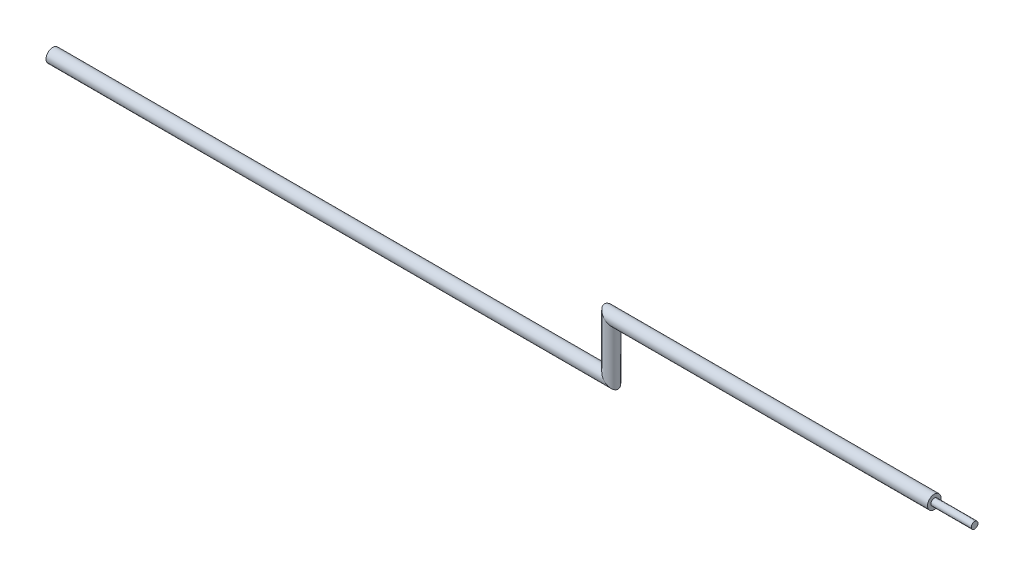
SolidWorks part; units mm, degrees
ref_plane "Front Plane" through (0, 0, 0) normal (0, 0, 1) x (1, 0, 0)
ref_plane "Top Plane" through (0, 0, 0) normal (0, 1, 0) x (1, 0, 0)
ref_plane "Right Plane" through (0, 0, 0) normal (1, 0, 0) x (0, 0, -1)
sketch "Sketch1" plane through (0, 0, 0) normal (0, 0, 1) x (1, 0, 0)
  line L0 (527.05, 0) -> (0, 0)
  line L1 (527.05, 0) -> (527.05, 50.8)
  line L2 (527.05, 50.8) -> (831.85, 50.8)
  point P4 (0, 0)
  dimension "D1" = 527.05
  dimension "D2" = 50.8
  dimension "D3" = 304.8
sweep "Sweep1" add path "Sketch1" circular profile diameter 12.7 parameters "D3"=12.7
sketch "Sketch20" plane through (831.85, 0, 0) normal (1, 0, 0) x (0, 0, -1)
  circle A0 centre (0, 50.8) radius 3.175
  circle A1 centre (0, 50.8) radius 6.35 construction
  point P3 (0, 0)
  dimension "D1" = 6.35
extrude "Boss-Extrude3" add sketch "Sketch20" along normal blind 38.1
